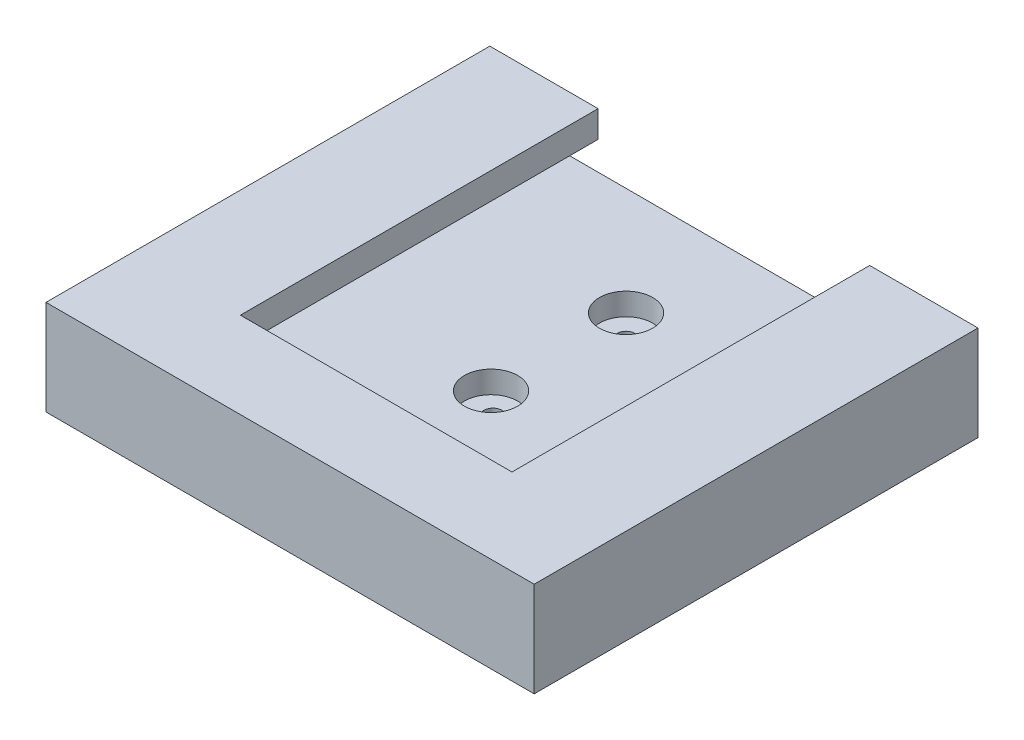
SolidWorks part; units mm, degrees
ref_plane "Front Plane" through (0, 0, 0) normal (0, 0, 1) x (1, 0, 0)
ref_plane "Top Plane" through (0, 0, 0) normal (0, 1, 0) x (1, 0, 0)
ref_plane "Right Plane" through (0, 0, 0) normal (1, 0, 0) x (0, 0, -1)
sketch "Sketch1" plane through (0, 0, 0) normal (0, 1, 0) x (1, 0, 0)
  line L1 (-27.5, 25) -> (27.5, 25)
  line L2 (-27.5, 25) -> (-27.5, -25)
  line L3 (-27.5, -25) -> (27.5, -25)
  line L4 (27.5, 25) -> (27.5, -25)
  line L5 (-27.5, 25) -> (27.5, -25) construction
  line L6 (-27.5, -25) -> (27.5, 25) construction
  point P0 (0, 0)
  dimension "D1" = 50
  dimension "D2" = 55
extrude "Boss-Extrude1" add sketch "Sketch1" along normal blind 10.7
sketch "Sketch2" plane through (0, 10.7, 0) normal (0, 1, 0) x (1, 0, 0)
  line L0 (27.5, 25) -> (-27.5, 25) construction
  line L1 (-15.3, 25) -> (15.3, 25)
  line L2 (-15.3, 25) -> (-15.3, -15.3)
  line L3 (-15.3, -15.3) -> (15.3, -15.3)
  line L4 (15.3, 25) -> (15.3, -15.3)
  line L5 (-27.5, 25) -> (-27.5, -25) construction
  dimension "D1" = 30.6
  dimension "D2" = 40.3
  dimension "D3" = 12.2
extrude "Cut-Extrude2" cut sketch "Sketch2" against normal blind 3
sketch "Sketch4" plane through (0, 7.7, 0) normal (0, 1, 0) x (1, 0, 0)
  line L0 (15.3, 25) -> (-15.3, 25) construction
  line L1 (-20.3, 25) -> (20.3, 25)
  line L2 (-20.3, 25) -> (-20.3, -15.3)
  line L3 (-20.3, -15.3) -> (20.3, -15.3)
  line L4 (20.3, 25) -> (20.3, -15.3)
  line L5 (-27.5, 25) -> (-27.5, -25) construction
  dimension "D1" = 40.6
  dimension "D2" = 40.3
  dimension "D3" = 7.2
extrude "Cut-Extrude3" cut sketch "Sketch4" against normal blind 3.2
sketch "Sketch13" plane through (0, 4.5, 0) normal (0, 1, 0) x (1, 0, 0)
  circle A0 centre (0, 12.8503) radius 3
  circle A1 centre (0, -2.3599) radius 3
  dimension "D1" = 6
  dimension "D2" = 6
extrude "Cut-Extrude4" cut sketch "Sketch13" against normal blind 2.5
sketch "Sketch14" plane through (0, 2, 0) normal (0, 1, 0) x (1, 0, 0)
  circle A0 centre (0, 12.8503) radius 1
  circle A1 centre (0, -2.1497) radius 1
  dimension "D1" = 2
  dimension "D2" = 2
  dimension "D3" = 15
extrude "Cut-Extrude5" cut sketch "Sketch14" against normal up to surface (2 mm away) up to face at (0, 0, 0)
